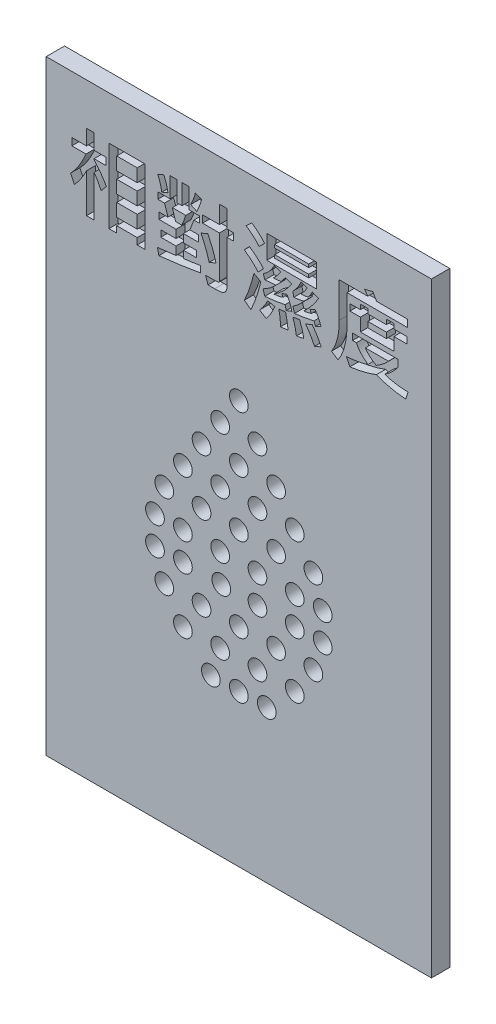
SolidWorks part; units mm, degrees
ref_plane "前基準面" through (0, 0, 0) normal (0, 0, 1) x (1, 0, 0)
ref_plane "上基準面" through (0, 0, 0) normal (0, 1, 0) x (1, 0, 0)
ref_plane "右基準面" through (0, 0, 0) normal (1, 0, 0) x (0, 0, -1)
sketch "草圖4" plane through (0, 0, 0) normal (0, 0, 1) x (1, 0, 0)
  line L1 (0, 0) -> (105, 0)
  line L2 (0, 0) -> (0, 165)
  line L3 (0, 165) -> (105, 165)
  line L4 (105, 0) -> (105, 165)
extrude "填料-伸長2" add sketch "草圖4" along normal blind 5
sketch "草圖11" plane through (0, 0, 5) normal (0, 0, 1) x (1, 0, 0)
  circle A0 centre (52.5, 110) radius 2.55
  circle A1 centre (47.42, 102.38) radius 2.55
  circle A2 centre (57.58, 102.38) radius 2.55
  circle A3 centre (62.66, 94.76) radius 2.55
  circle A4 centre (42.34, 94.76) radius 2.55
  circle A5 centre (57.58, 87.14) radius 2.55
  circle A6 centre (67.74, 87.14) radius 2.55
  circle A7 centre (47.42, 87.14) radius 2.55
  circle A8 centre (52.5, 79.52) radius 2.55
  circle A9 centre (75.36, 71.9) radius 2.55
  circle A10 centre (52.5, 94.76) radius 2.55
  circle A12 centre (47.42, 71.9) radius 2.55
  circle A13 centre (67.74, 71.9) radius 2.55
  circle A14 centre (37.26, 71.9) radius 2.55
  circle A15 centre (29.64, 71.9) radius 2.55
  circle A16 centre (57.58, 71.9) radius 2.55
  circle A17 centre (47.72, 64.28) radius 2.55
  circle A18 centre (57.58, 64.28) radius 2.55
  circle A19 centre (37.26, 64.28) radius 2.55
  circle A20 centre (29.64, 64.28) radius 2.55
  circle A21 centre (67.74, 64.28) radius 2.55
  circle A22 centre (75.36, 64.28) radius 2.55
  circle A24 centre (32.18, 56.66) radius 2.55
  circle A25 centre (42.34, 56.66) radius 2.55
  circle A26 centre (52.5, 56.66) radius 2.55
  circle A27 centre (62.66, 56.66) radius 2.55
  circle A28 centre (72.82, 56.66) radius 2.55
  circle A30 centre (37.26, 49.04) radius 2.55
  circle A31 centre (47.42, 49.04) radius 2.55
  circle A32 centre (57.58, 49.04) radius 2.55
  circle A33 centre (67.74, 49.04) radius 2.55
  circle A35 centre (44.88, 41.42) radius 2.55
  circle A36 centre (52.5, 41.42) radius 2.55
  circle A37 centre (60.12, 41.42) radius 2.55
  circle A41 centre (37.26, 87.14) radius 2.55
  circle A42 centre (42.34, 79.52) radius 2.55
  circle A43 centre (32.18, 79.52) radius 2.55
  circle A44 centre (72.82, 79.52) radius 2.55
  circle A45 centre (62.66, 79.52) radius 2.55
  point P22 (0, 0)
extrude "除料-伸長6" cut sketch "草圖11" against normal through all contours A0 | A15 | A20 | A18 | A22 | A21 | A27 | A26 | A24 | A30 | A36 | A37 | A4 | A1 | A2 | A10 | A3 | A5 | A6 | A7 | A41 | A43 | A42 | A8 | A45 | A44 | A9 | A13 | A16 | A12 | A14 | A19 | A17 | A28 | A25 | A35 | A31 | A32 | A33
sketch "草圖12" plane through (0, 0, 5) normal (0, 0, 1) x (1, 0, 0)
  text T0 "相對濕度" font "微軟正黑體" height 18
extrude "除料-伸長7" cut sketch "草圖12" against normal blind 2.5
